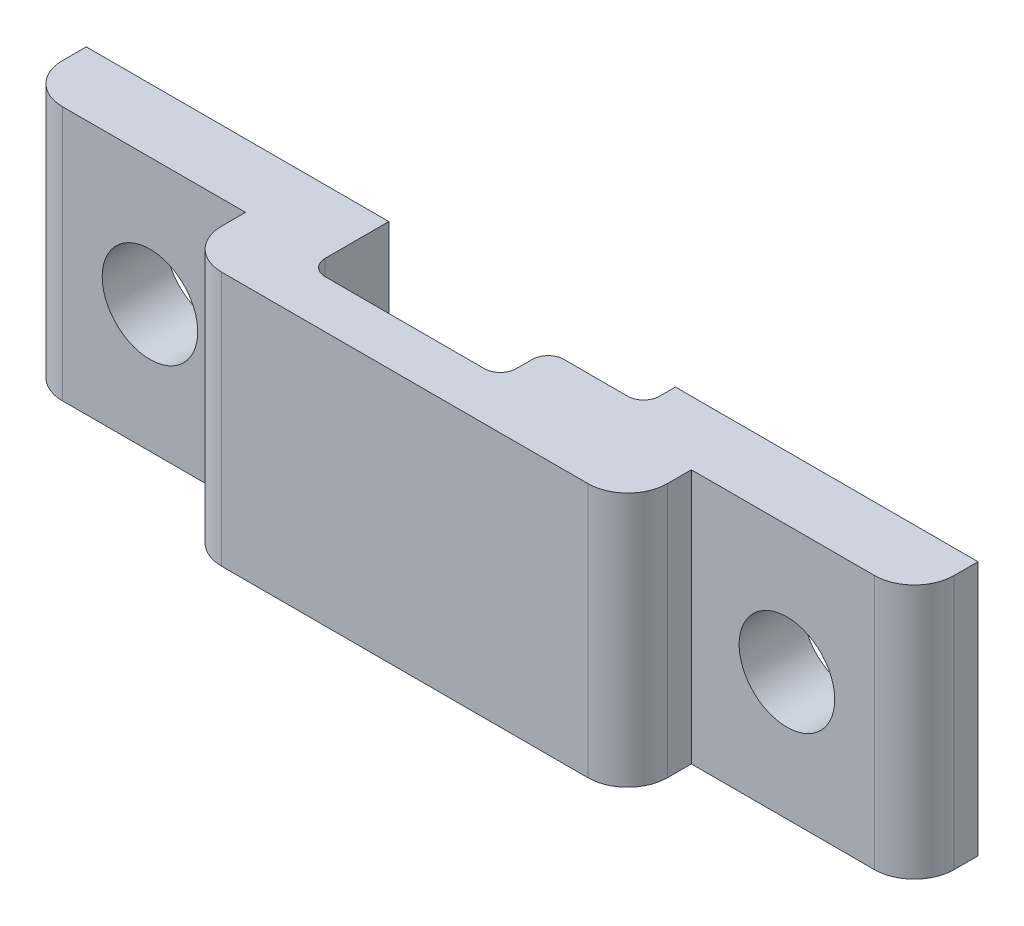
SolidWorks part; units mm, degrees
material "PET"
ref_plane "Front Plane" through (0, 0, 0) normal (0, 0, 1) x (1, 0, 0)
ref_plane "Top Plane" through (0, 0, 0) normal (0, 1, 0) x (1, 0, 0)
ref_plane "Right Plane" through (0, 0, 0) normal (1, 0, 0) x (0, 0, -1)
sketch "Sketch1" plane through (0, 0, 0) normal (0, 0, 1) x (1, 0, 0)
  line L0 (-12.7, 0) -> (0, 0) construction
  line L1 (0, 0) -> (12.7, 0) construction
  line L3 (-17.78, 5.08) -> (17.78, 5.08)
  line L4 (-17.78, 5.08) -> (-17.78, -5.08)
  line L5 (-17.78, -5.08) -> (17.78, -5.08)
  line L6 (17.78, 5.08) -> (17.78, -5.08)
  circle A0 centre (-12.7, 0) radius 1.905
  circle A1 centre (12.7, 0) radius 1.905
  dimension "D1" = 3.81
  dimension "D2" = 3.81
  dimension "D3" = 25.4
  dimension "D4" = 5.08
  dimension "D5" = 5.08
  dimension "D6" = 5.08
  dimension "D7" = 5.08
extrude "Boss-Extrude1" add sketch "Sketch1" along normal blind 5.08
sketch "Sketch2" plane through (0, -5.08, 0) normal (0, -1, 0) x (1, 0, 0)
  line L0 (0, 0) -> (-5.715, 0)
  line L5 (-17.78, 0) -> (17.78, 0) construction
  line L6 (-5.715, 0) -> (-5.715, 3.175)
  line L7 (-5.715, 3.175) -> (1.905, 3.175)
  line L8 (1.905, 3.175) -> (1.905, 1.27)
  line L9 (1.905, 1.27) -> (5.715, 1.27)
  line L10 (5.715, 1.27) -> (5.715, 0)
  line L11 (5.715, 0) -> (0, 0)
  line L13 (-17.78, 5.08) -> (-8.89, 5.08)
  line L14 (-17.78, 5.08) -> (-17.78, 2.54)
  line L15 (-17.78, 2.54) -> (-8.89, 2.54)
  line L16 (-8.89, 5.08) -> (-8.89, 2.54)
  line L17 (17.78, 5.08) -> (8.89, 5.08)
  line L18 (17.78, 5.08) -> (17.78, 2.54)
  line L19 (17.78, 2.54) -> (8.89, 2.54)
  line L20 (8.89, 5.08) -> (8.89, 2.54)
  point P0 (0, 0)
  dimension "D1" = 7.62
  dimension "D2" = 3.81
  dimension "D3" = 5.715
  dimension "D4" = 1.27
  dimension "D5" = 3.175
  dimension "D6" = 2.54
  dimension "D7" = 8.89
sketch "Sketch3" plane through (0, 0, 5.08) normal (0, 0, 1) x (1, 0, 0)
  line L0 (-12.7, 0) -> (-9.271, 0) construction
  line L1 (-9.271, 0) -> (-9.271, -5.08) construction
  line L2 (-17.78, -5.08) -> (-8.89, -5.08) construction
  circle A0 centre (-12.7, 0) radius 3.429 construction
  point P8 (-9.271, 0)
  dimension "D1" = 6.858
extrude "Cut-Extrude1" cut sketch "Sketch2" against normal through all contours L15 L16 L13 L14 | L6 L7 L8 L9 L10 L11 L0 | L20 L19 L18 L17
fillet "Fillet1" radius 1.5875 4 edges at (-17.78, 0, 2.54) (17.78, 0, 2.54) (8.89, 0, 5.08) (-8.89, 0, 5.08)
fillet "Fillet2" radius 0.635 4 edges at (5.715, 0, 1.27) (1.905, 0, 1.27) (1.905, 0, 3.175) (-5.715, 0, 3.175)
equation "\"D3@Sketch2\"=(\"D1@Sketch2\"+\"D2@Sketch2\")/2"
